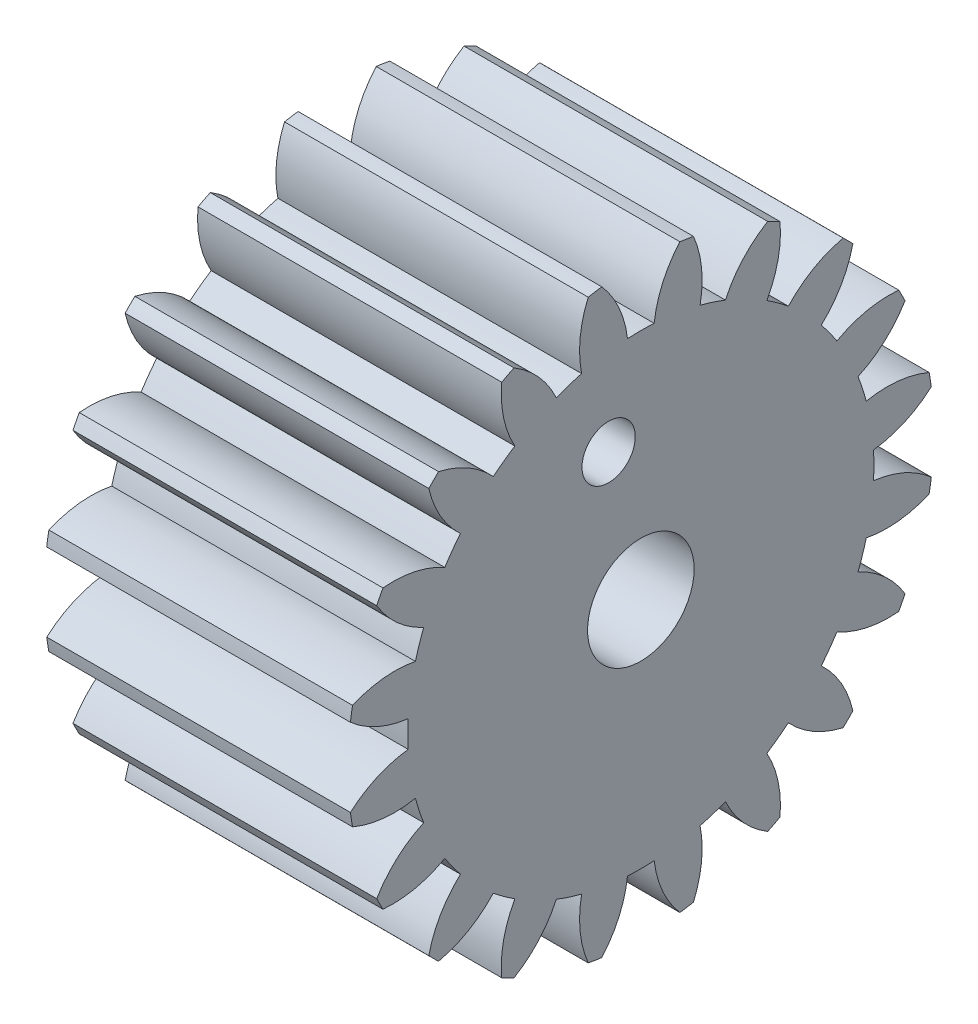
SolidWorks part; units mm, degrees
ref_plane "前视基准面" through (0, 0, 0) normal (0, 0, 1) x (1, 0, 0)
ref_plane "上视基准面" through (0, 0, 0) normal (0, 1, 0) x (1, 0, 0)
ref_plane "右视基准面" through (0, 0, 0) normal (1, 0, 0) x (0, 0, -1)
sketch "草图7" plane through (0, 0, 0) normal (1, 0, 0) x (0, 0, -1)
  arc A0 (-5.451, 0.7325) -> (-4.3669, 0.2499) centre (-4.1322, 2.2361) ccw
  arc A1 (-4.3669, 0.2499) -> (-4.3669, -0.2499) centre (0, 0) ccw
  arc A2 (-4.3669, -0.2499) -> (-5.451, -0.7325) centre (-4.1322, -2.2361) ccw
  arc A3 (-5.451, -0.7325) -> (-5.4106, -0.9878) centre (0, 0) ccw
  arc A4 (-5.4106, -0.9878) -> (-4.2304, -1.1118) centre (-4.621, 0.8497) ccw
  arc A5 (-4.2304, -1.1118) -> (-4.0759, -1.5871) centre (0, 0) ccw
  arc A6 (-4.0759, -1.5871) -> (-4.9579, -2.3811) centre (-3.239, -3.4036) ccw
  arc A7 (-4.9579, -2.3811) -> (-4.8405, -2.6114) centre (0, 0) ccw
  arc A8 (-4.8405, -2.6114) -> (-3.6797, -2.3646) centre (-4.6574, -0.6198) ccw
  arc A9 (-3.6797, -2.3646) -> (-3.386, -2.7689) centre (0, 0) ccw
  arc A10 (-3.386, -2.7689) -> (-3.9794, -3.7966) centre (-2.0287, -4.2379) ccw
  arc A11 (-3.9794, -3.7966) -> (-3.7966, -3.9794) centre (0, 0) ccw
  arc A12 (-3.7966, -3.9794) -> (-2.7689, -3.386) centre (-4.2379, -2.0287) ccw
  arc A13 (-2.7689, -3.386) -> (-2.3646, -3.6797) centre (0, 0) ccw
  arc A14 (-2.3646, -3.6797) -> (-2.6114, -4.8405) centre (-0.6198, -4.6574) ccw
  arc A15 (-2.6114, -4.8405) -> (-2.3811, -4.9579) centre (0, 0) ccw
  arc A16 (-2.3811, -4.9579) -> (-1.5871, -4.0759) centre (-3.4036, -3.239) ccw
  arc A17 (-1.5871, -4.0759) -> (-1.1118, -4.2304) centre (0, 0) ccw
  arc A18 (-1.1118, -4.2304) -> (-0.9878, -5.4106) centre (0.8497, -4.621) ccw
  arc A19 (-0.9878, -5.4106) -> (-0.7325, -5.451) centre (0, 0) ccw
  arc A20 (-0.7325, -5.451) -> (-0.2499, -4.3669) centre (-2.2361, -4.1322) ccw
  arc A21 (-0.2499, -4.3669) -> (0.2499, -4.3669) centre (0, 0) ccw
  arc A22 (0.2499, -4.3669) -> (0.7325, -5.451) centre (2.2361, -4.1322) ccw
  arc A23 (0.7325, -5.451) -> (0.9878, -5.4106) centre (0, 0) ccw
  arc A24 (0.9878, -5.4106) -> (1.1118, -4.2304) centre (-0.8497, -4.621) ccw
  arc A25 (1.1118, -4.2304) -> (1.5871, -4.0759) centre (0, 0) ccw
  arc A26 (1.5871, -4.0759) -> (2.3811, -4.9579) centre (3.4036, -3.239) ccw
  arc A27 (2.3811, -4.9579) -> (2.6114, -4.8405) centre (0, 0) ccw
  arc A28 (2.6114, -4.8405) -> (2.3646, -3.6797) centre (0.6198, -4.6574) ccw
  arc A29 (2.3646, -3.6797) -> (2.7689, -3.386) centre (0, 0) ccw
  arc A30 (2.7689, -3.386) -> (3.7966, -3.9794) centre (4.2379, -2.0287) ccw
  arc A31 (3.7966, -3.9794) -> (3.9794, -3.7966) centre (0, 0) ccw
  arc A32 (3.9794, -3.7966) -> (3.386, -2.7689) centre (2.0287, -4.2379) ccw
  arc A33 (3.386, -2.7689) -> (3.6797, -2.3646) centre (0, 0) ccw
  arc A34 (3.6797, -2.3646) -> (4.8405, -2.6114) centre (4.6574, -0.6198) ccw
  arc A35 (4.8405, -2.6114) -> (4.9579, -2.3811) centre (0, 0) ccw
  arc A36 (4.9579, -2.3811) -> (4.0759, -1.5871) centre (3.239, -3.4036) ccw
  arc A37 (4.0759, -1.5871) -> (4.2304, -1.1118) centre (0, 0) ccw
  arc A38 (4.2304, -1.1118) -> (5.4106, -0.9878) centre (4.621, 0.8497) ccw
  arc A39 (5.4106, -0.9878) -> (5.451, -0.7325) centre (0, 0) ccw
  arc A40 (5.451, -0.7325) -> (4.3669, -0.2499) centre (4.1322, -2.2361) ccw
  arc A41 (4.3669, -0.2499) -> (4.3669, 0.2499) centre (0, 0) ccw
  arc A42 (4.3669, 0.2499) -> (5.451, 0.7325) centre (4.1322, 2.2361) ccw
  arc A43 (5.451, 0.7325) -> (5.4106, 0.9878) centre (0, 0) ccw
  arc A44 (5.4106, 0.9878) -> (4.2304, 1.1118) centre (4.621, -0.8497) ccw
  arc A45 (4.2304, 1.1118) -> (4.0759, 1.5871) centre (0, 0) ccw
  arc A46 (4.0759, 1.5871) -> (4.9579, 2.3811) centre (3.239, 3.4036) ccw
  arc A47 (4.9579, 2.3811) -> (4.8405, 2.6114) centre (0, 0) ccw
  arc A48 (4.8405, 2.6114) -> (3.6797, 2.3646) centre (4.6574, 0.6198) ccw
  arc A49 (3.6797, 2.3646) -> (3.386, 2.7689) centre (0, 0) ccw
  arc A50 (3.386, 2.7689) -> (3.9794, 3.7966) centre (2.0287, 4.2379) ccw
  arc A51 (3.9794, 3.7966) -> (3.7966, 3.9794) centre (0, 0) ccw
  arc A52 (3.7966, 3.9794) -> (2.7689, 3.386) centre (4.2379, 2.0287) ccw
  arc A53 (2.7689, 3.386) -> (2.3646, 3.6797) centre (0, 0) ccw
  arc A54 (2.3646, 3.6797) -> (2.6114, 4.8405) centre (0.6198, 4.6574) ccw
  arc A55 (2.6114, 4.8405) -> (2.3811, 4.9579) centre (0, 0) ccw
  arc A56 (2.3811, 4.9579) -> (1.5871, 4.0759) centre (3.4036, 3.239) ccw
  arc A57 (1.5871, 4.0759) -> (1.1118, 4.2304) centre (0, 0) ccw
  arc A58 (1.1118, 4.2304) -> (0.9878, 5.4106) centre (-0.8497, 4.621) ccw
  arc A59 (0.9878, 5.4106) -> (0.7325, 5.451) centre (0, 0) ccw
  arc A60 (0.7325, 5.451) -> (0.2499, 4.3669) centre (2.2361, 4.1322) ccw
  arc A61 (0.2499, 4.3669) -> (-0.2499, 4.3669) centre (0, 0) ccw
  arc A62 (-0.2499, 4.3669) -> (-0.7325, 5.451) centre (-2.2361, 4.1322) ccw
  arc A63 (-0.7325, 5.451) -> (-0.9878, 5.4106) centre (0, 0) ccw
  arc A64 (-0.9878, 5.4106) -> (-1.1118, 4.2304) centre (0.8497, 4.621) ccw
  arc A65 (-1.1118, 4.2304) -> (-1.5871, 4.0759) centre (0, 0) ccw
  arc A66 (-1.5871, 4.0759) -> (-2.3811, 4.9579) centre (-3.4036, 3.239) ccw
  arc A67 (-2.3811, 4.9579) -> (-2.6114, 4.8405) centre (0, 0) ccw
  arc A68 (-2.6114, 4.8405) -> (-2.3646, 3.6797) centre (-0.6198, 4.6574) ccw
  arc A69 (-2.3646, 3.6797) -> (-2.7689, 3.386) centre (0, 0) ccw
  arc A70 (-2.7689, 3.386) -> (-3.7966, 3.9794) centre (-4.2379, 2.0287) ccw
  arc A71 (-3.7966, 3.9794) -> (-3.9794, 3.7966) centre (0, 0) ccw
  arc A72 (-3.9794, 3.7966) -> (-3.386, 2.7689) centre (-2.0287, 4.2379) ccw
  arc A73 (-3.386, 2.7689) -> (-3.6797, 2.3646) centre (0, 0) ccw
  arc A74 (-3.6797, 2.3646) -> (-4.8405, 2.6114) centre (-4.6574, 0.6198) ccw
  arc A75 (-4.8405, 2.6114) -> (-4.9579, 2.3811) centre (0, 0) ccw
  arc A76 (-4.9579, 2.3811) -> (-4.0759, 1.5871) centre (-3.239, 3.4036) ccw
  arc A77 (-4.0759, 1.5871) -> (-4.2304, 1.1118) centre (0, 0) ccw
  arc A78 (-4.2304, 1.1118) -> (-5.4106, 0.9878) centre (-4.621, -0.8497) ccw
  arc A79 (-5.4106, 0.9878) -> (-5.451, 0.7325) centre (0, 0) ccw
  circle A80 centre (0, 0) radius 1
  circle A81 centre (-0.6051, 2.7031) radius 0.5
  circle A82 centre (0, 0) radius 0.2517 construction
  dimension "D1" = 4.374
  dimension "D2" = 2
  dimension "D3" = 1
  dimension "D4" = 2.77
extrude "凸台-拉伸3" add sketch "草图7" along normal blind 5.7
